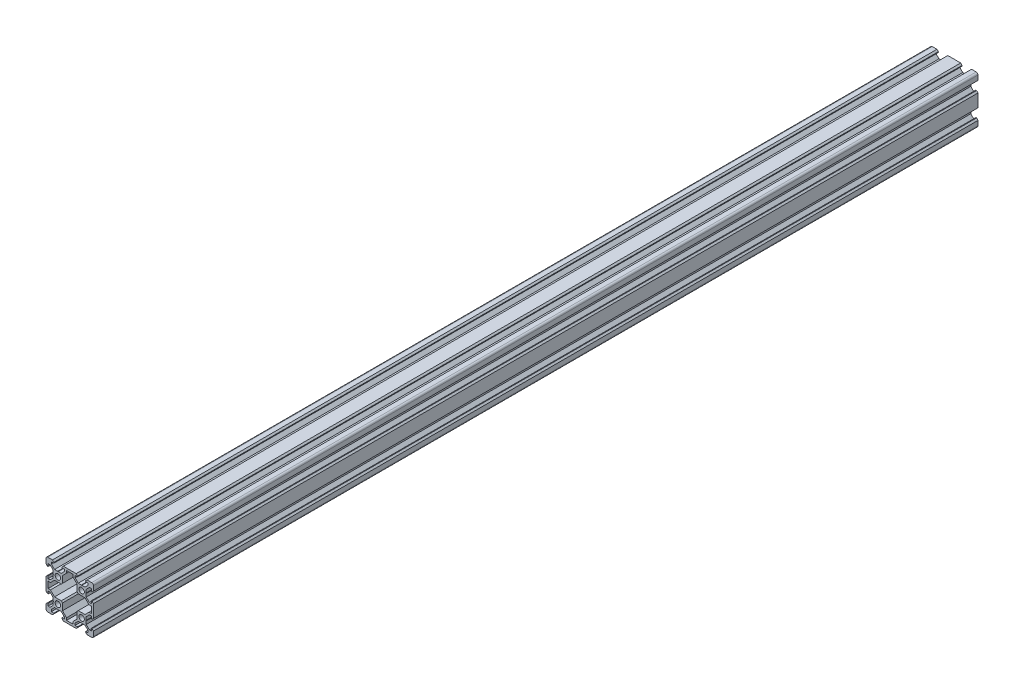
SolidWorks part; units mm, degrees
ref_plane "Front Plane" through (0, 0, 0) normal (0, 0, 1) x (1, 0, 0)
ref_plane "Top Plane" through (0, 0, 0) normal (0, 1, 0) x (1, 0, 0)
ref_plane "Right Plane" through (0, 0, 0) normal (1, 0, 0) x (0, 0, -1)
sketch "Sketch1" plane through (0, 0, 0) normal (0, 0, 1) x (1, 0, 0)
  line L0 (-12.4674, 6.4719) -> (-6.7887, 6.4719)
  line L1 (-15.8674, 3.0719) -> (-12.4674, 6.4719)
  line L2 (-17.8281, 3.0719) -> (-15.8674, 3.0719)
  line L3 (-17.8281, -2.3281) -> (-17.8281, 3.0719)
  line L4 (-17.8281, -2.3281) -> (-15.8674, -2.3281)
  line L5 (-15.8674, -2.3281) -> (-12.4674, -5.7281)
  line L6 (-12.4674, -5.7281) -> (-6.7887, -5.7281)
  line L7 (-5.7281, -6.7887) -> (-6.7887, -5.7281)
  line L8 (-5.7281, -12.4674) -> (-5.7281, -6.7887)
  line L9 (-2.3281, -15.8674) -> (-5.7281, -12.4674)
  line L10 (-2.3281, -17.8281) -> (-2.3281, -15.8674)
  line L11 (3.0719, -17.8281) -> (-2.3281, -17.8281)
  line L12 (3.0719, -17.8281) -> (3.0719, -15.8674)
  line L13 (3.0719, -15.8674) -> (6.4719, -12.4674)
  line L14 (6.4719, -12.4674) -> (6.4719, -6.7887)
  line L15 (7.5326, -5.7281) -> (6.4719, -6.7887)
  line L16 (13.2113, -5.7281) -> (7.5326, -5.7281)
  line L17 (16.6113, -2.3281) -> (13.2113, -5.7281)
  line L18 (18.5719, -2.3281) -> (16.6113, -2.3281)
  line L19 (18.5719, -2.3281) -> (18.5719, 3.0719)
  line L20 (18.5719, 3.0719) -> (16.6113, 3.0719)
  line L21 (16.6113, 3.0719) -> (13.2113, 6.4719)
  line L22 (13.2113, 6.4719) -> (7.5326, 6.4719)
  line L23 (6.4719, 13.2113) -> (6.4719, 7.5326)
  line L24 (6.4719, 7.5326) -> (7.5326, 6.4719)
  line L25 (3.0719, 16.6113) -> (6.4719, 13.2113)
  line L26 (3.0719, 18.5719) -> (3.0719, 16.6113)
  line L27 (3.0719, 18.5719) -> (-2.3281, 18.5719)
  line L28 (-2.3281, 18.5719) -> (-2.3281, 16.6113)
  line L29 (-2.3281, 16.6113) -> (-5.7281, 13.2113)
  line L30 (-5.7281, 13.2113) -> (-5.7281, 7.5326)
  line L31 (-6.7887, 6.4719) -> (-5.7281, 7.5326)
  line L32 (14.2719, -9.8381) -> (14.0619, -9.6281)
  line L33 (14.0619, -9.6281) -> (14.2719, -9.4181)
  line L34 (14.2719, -9.4181) -> (14.2719, -6.7887)
  line L35 (14.2719, -6.7887) -> (16.9326, -4.1281)
  line L36 (16.9326, -4.1281) -> (18.5719, -4.1281)
  line L37 (18.5719, -4.1281) -> (18.5719, -6.2331)
  line L38 (18.5719, -6.2331) -> (19.1869, -6.2331)
  line L39 (19.1869, -6.2331) -> (20.3719, -5.0481)
  line L40 (20.3719, -5.0481) -> (20.3719, 5.7919)
  line L41 (20.3719, 5.7919) -> (19.1869, 6.9769)
  line L42 (19.1869, 6.9769) -> (18.5719, 6.9769)
  line L43 (18.5719, 6.9769) -> (18.5719, 4.8719)
  line L44 (18.5719, 4.8719) -> (16.9326, 4.8719)
  line L45 (16.9326, 4.8719) -> (14.2719, 7.5326)
  line L46 (14.2719, 7.5326) -> (14.2719, 10.1619)
  line L47 (14.2719, 10.1619) -> (14.0619, 10.3719)
  line L48 (14.0619, 10.3719) -> (14.2719, 10.5819)
  line L49 (14.2719, 10.5819) -> (14.2719, 13.2113)
  line L50 (14.2719, 13.2113) -> (16.9326, 15.8719)
  line L51 (16.9326, 15.8719) -> (18.5719, 15.8719)
  line L52 (18.5719, 15.8719) -> (18.5719, 13.7669)
  line L53 (18.5719, 13.7669) -> (19.1869, 13.7669)
  line L54 (19.1869, 13.7669) -> (20.3719, 14.9519)
  line L55 (20.3719, 14.9519) -> (20.3719, 18.8719)
  line L56 (18.8719, 20.3719) -> (14.9519, 20.3719)
  line L57 (14.9519, 20.3719) -> (13.7669, 19.1869)
  line L58 (13.7669, 19.1869) -> (13.7669, 18.5719)
  line L59 (13.7669, 18.5719) -> (15.8719, 18.5719)
  line L60 (15.8719, 18.5719) -> (15.8719, 16.9326)
  line L61 (15.8719, 16.9326) -> (13.2113, 14.2719)
  line L62 (13.2113, 14.2719) -> (10.5819, 14.2719)
  line L63 (10.5819, 14.2719) -> (10.3719, 14.0619)
  line L64 (10.3719, 14.0619) -> (10.1619, 14.2719)
  line L65 (10.1619, 14.2719) -> (7.5326, 14.2719)
  line L66 (7.5326, 14.2719) -> (4.8719, 16.9326)
  line L67 (4.8719, 16.9326) -> (4.8719, 18.5719)
  line L68 (4.8719, 18.5719) -> (6.9769, 18.5719)
  line L69 (6.9769, 18.5719) -> (6.9769, 19.1869)
  line L70 (6.9769, 19.1869) -> (5.7919, 20.3719)
  line L71 (5.7919, 20.3719) -> (-5.0481, 20.3719)
  line L72 (-5.0481, 20.3719) -> (-6.2331, 19.1869)
  line L73 (-6.2331, 19.1869) -> (-6.2331, 18.5719)
  line L74 (-6.2331, 18.5719) -> (-4.1281, 18.5719)
  line L75 (-4.1281, 18.5719) -> (-4.1281, 16.9326)
  line L76 (-4.1281, 16.9326) -> (-6.7887, 14.2719)
  line L77 (-6.7887, 14.2719) -> (-9.4181, 14.2719)
  line L78 (-9.4181, 14.2719) -> (-9.6281, 14.0619)
  line L79 (-9.6281, 14.0619) -> (-9.8381, 14.2719)
  line L80 (-9.8381, 14.2719) -> (-12.4674, 14.2719)
  line L81 (-12.4674, 14.2719) -> (-15.1281, 16.9326)
  line L82 (-15.1281, 16.9326) -> (-15.1281, 18.5719)
  line L83 (-15.1281, 18.5719) -> (-13.0231, 18.5719)
  line L84 (-13.0231, 18.5719) -> (-13.0231, 19.1869)
  line L85 (-13.0231, 19.1869) -> (-14.2081, 20.3719)
  line L86 (-14.2081, 20.3719) -> (-18.1281, 20.3719)
  line L87 (-19.6281, 18.8719) -> (-19.6281, 14.9519)
  line L88 (-19.6281, 14.9519) -> (-18.4431, 13.7669)
  line L89 (-18.4431, 13.7669) -> (-17.8281, 13.7669)
  line L90 (-17.8281, 13.7669) -> (-17.8281, 15.8719)
  line L91 (-17.8281, 15.8719) -> (-16.1887, 15.8719)
  line L92 (-16.1887, 15.8719) -> (-13.5281, 13.2113)
  line L93 (-13.5281, 13.2113) -> (-13.5281, 10.5819)
  line L94 (-13.5281, 10.5819) -> (-13.3181, 10.3719)
  line L95 (-13.3181, 10.3719) -> (-13.5281, 10.1619)
  line L96 (-13.5281, 10.1619) -> (-13.5281, 7.5326)
  line L97 (-13.5281, 7.5326) -> (-16.1887, 4.8719)
  line L98 (-16.1887, 4.8719) -> (-17.8281, 4.8719)
  line L99 (-17.8281, 4.8719) -> (-17.8281, 6.9769)
  line L100 (-17.8281, 6.9769) -> (-18.4431, 6.9769)
  line L101 (-18.4431, 6.9769) -> (-19.6281, 5.7919)
  line L102 (-19.6281, 5.7919) -> (-19.6281, -5.0481)
  line L103 (-19.6281, -5.0481) -> (-18.4431, -6.2331)
  line L104 (-18.4431, -6.2331) -> (-17.8281, -6.2331)
  line L105 (-17.8281, -6.2331) -> (-17.8281, -4.1281)
  line L106 (-17.8281, -4.1281) -> (-16.1887, -4.1281)
  line L107 (-16.1887, -4.1281) -> (-13.5281, -6.7887)
  line L108 (-13.5281, -6.7887) -> (-13.5281, -9.4181)
  line L109 (-13.5281, -9.4181) -> (-13.3181, -9.6281)
  line L110 (-13.3181, -9.6281) -> (-13.5281, -9.8381)
  line L111 (-13.5281, -9.8381) -> (-13.5281, -12.4674)
  line L112 (-13.5281, -12.4674) -> (-16.1887, -15.1281)
  line L113 (-16.1887, -15.1281) -> (-17.8281, -15.1281)
  line L114 (-17.8281, -15.1281) -> (-17.8281, -13.0231)
  line L115 (-17.8281, -13.0231) -> (-18.4431, -13.0231)
  line L116 (-18.4431, -13.0231) -> (-19.6281, -14.2081)
  line L117 (-19.6281, -14.2081) -> (-19.6281, -18.1281)
  line L118 (-18.1281, -19.6281) -> (-14.2081, -19.6281)
  line L119 (-14.2081, -19.6281) -> (-13.0231, -18.4431)
  line L120 (-13.0231, -18.4431) -> (-13.0231, -17.8281)
  line L121 (-13.0231, -17.8281) -> (-15.1281, -17.8281)
  line L122 (-15.1281, -17.8281) -> (-15.1281, -16.1887)
  line L123 (-15.1281, -16.1887) -> (-12.4674, -13.5281)
  line L124 (-12.4674, -13.5281) -> (-9.8381, -13.5281)
  line L125 (-9.8381, -13.5281) -> (-9.6281, -13.3181)
  line L126 (-9.6281, -13.3181) -> (-9.4181, -13.5281)
  line L127 (-9.4181, -13.5281) -> (-6.7887, -13.5281)
  line L128 (-6.7887, -13.5281) -> (-4.1281, -16.1887)
  line L129 (-4.1281, -16.1887) -> (-4.1281, -17.8281)
  line L130 (-4.1281, -17.8281) -> (-6.2331, -17.8281)
  line L131 (-6.2331, -17.8281) -> (-6.2331, -18.4431)
  line L132 (-6.2331, -18.4431) -> (-5.0481, -19.6281)
  line L133 (-5.0481, -19.6281) -> (5.7919, -19.6281)
  line L134 (5.7919, -19.6281) -> (6.9769, -18.4431)
  line L135 (6.9769, -18.4431) -> (6.9769, -17.8281)
  line L136 (6.9769, -17.8281) -> (4.8719, -17.8281)
  line L137 (4.8719, -17.8281) -> (4.8719, -16.1887)
  line L138 (4.8719, -16.1887) -> (7.5326, -13.5281)
  line L139 (7.5326, -13.5281) -> (10.1619, -13.5281)
  line L140 (10.1619, -13.5281) -> (10.3719, -13.3181)
  line L141 (10.3719, -13.3181) -> (10.5819, -13.5281)
  line L142 (10.5819, -13.5281) -> (13.2113, -13.5281)
  line L143 (13.2113, -13.5281) -> (15.8719, -16.1887)
  line L144 (15.8719, -16.1887) -> (15.8719, -17.8281)
  line L145 (15.8719, -17.8281) -> (13.7669, -17.8281)
  line L146 (13.7669, -17.8281) -> (13.7669, -18.4431)
  line L147 (13.7669, -18.4431) -> (14.9519, -19.6281)
  line L148 (14.9519, -19.6281) -> (18.8719, -19.6281)
  line L149 (20.3719, -18.1281) -> (20.3719, -14.2081)
  line L150 (20.3719, -14.2081) -> (19.1869, -13.0231)
  line L151 (19.1869, -13.0231) -> (18.5719, -13.0231)
  line L152 (18.5719, -13.0231) -> (18.5719, -15.1281)
  line L153 (18.5719, -15.1281) -> (16.9326, -15.1281)
  line L154 (16.9326, -15.1281) -> (14.2719, -12.4674)
  line L155 (14.2719, -12.4674) -> (14.2719, -9.8381)
  arc A0 (20.3719, 18.8719) -> (18.8719, 20.3719) centre (18.8719, 18.8719) ccw
  arc A1 (-18.1281, 20.3719) -> (-19.6281, 18.8719) centre (-18.1281, 18.8719) ccw
  arc A2 (-19.6281, -18.1281) -> (-18.1281, -19.6281) centre (-18.1281, -18.1281) ccw
  arc A3 (18.8719, -19.6281) -> (20.3719, -18.1281) centre (18.8719, -18.1281) ccw
  circle A4 centre (-9.6281, -9.6281) radius 2.3
  circle A5 centre (10.3719, -9.6281) radius 2.3
  circle A6 centre (10.3719, 10.3719) radius 2.3
  circle A7 centre (-9.6281, 10.3719) radius 2.3
extrude "Boss-Extrude1" add sketch "Sketch1" along normal blind 745
